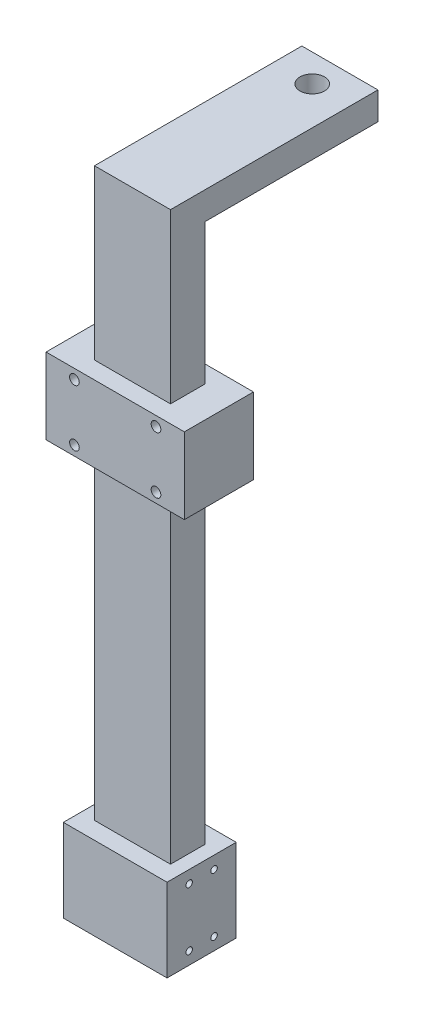
SolidWorks part; units mm, degrees
ref_plane "Front Plane" through (0, 0, 0) normal (0, 0, 1) x (1, 0, 0)
ref_plane "Top Plane" through (0, 0, 0) normal (0, 1, 0) x (1, 0, 0)
ref_plane "Right Plane" through (0, 0, 0) normal (1, 0, 0) x (0, 0, -1)
sketch "Sketch1" plane through (0, 0, 0) normal (0, 1, 0) x (1, 0, 0)
  line L1 (-6.985, -3.175) -> (6.985, -3.175)
  line L2 (-6.985, -3.175) -> (-6.985, 3.175)
  line L3 (-6.985, 3.175) -> (6.985, 3.175)
  line L4 (6.985, -3.175) -> (6.985, 3.175)
  line L5 (-6.985, -3.175) -> (6.985, 3.175) construction
  line L6 (-6.985, 3.175) -> (6.985, -3.175) construction
  point P0 (0, 0)
  dimension "D1" = 13.97
  dimension "D2" = 6.35
extrude "Boss-Extrude1" add sketch "Sketch1" along normal blind 114.3
sketch "Sketch3" plane through (0, 0, 3.175) normal (0, 0, 1) x (1, 0, 0)
  line L0 (0, 0) -> (0, 114.3) construction
  line L1 (-6.985, 114.3) -> (6.985, 114.3) construction
  line L3 (-12.7, 74.5062) -> (12.7, 74.5062)
  line L4 (-12.7, 74.5062) -> (-12.7, 88.4762)
  line L5 (-12.7, 88.4762) -> (12.7, 88.4762)
  line L6 (12.7, 74.5062) -> (12.7, 88.4762)
  line L7 (-12.7, 74.5062) -> (12.7, 88.4762) construction
  line L8 (-12.7, 88.4762) -> (12.7, 74.5062) construction
  point P5 (0, 81.4912)
  dimension "D1" = 13.97
  dimension "D2" = 25.4
extrude "Boss-Extrude3" add sketch "Sketch3" against normal blind 6.35
sketch "Sketch5" plane through (0, 0, 0) normal (1, 0, 0) x (0, 0, -1)
  line L0 (0, 0) -> (0, 74.5062) construction
  line L1 (3.175, 74.5062) -> (-3.175, 74.5062) construction
  line L2 (-3.175, 0) -> (3.175, 0) construction
  line L3 (-6.35, 0) -> (6.35, 0)
  line L4 (-6.35, 0) -> (-6.35, 15.24)
  line L5 (-6.35, 15.24) -> (6.35, 15.24)
  line L6 (6.35, 0) -> (6.35, 15.24)
  line L7 (-6.35, 0) -> (6.35, 15.24) construction
  line L8 (-6.35, 15.24) -> (6.35, 0) construction
  point P5 (0, 7.62)
  dimension "D1" = 12.7
  dimension "D2" = 15.24
extrude "Boss-Extrude5" add sketch "Sketch5" along normal blind 9.525 and the other way blind 9.525
sketch "Sketch6" plane through (0, 114.3, 0) normal (0, 1, 0) x (1, 0, 0)
  line L0 (6.985, -3.175) -> (6.985, 3.175) construction
  line L1 (-6.985, -3.175) -> (6.985, -3.175)
  line L2 (-6.985, -3.175) -> (-6.985, 34.925)
  line L3 (-6.985, 34.925) -> (6.985, 34.925)
  line L4 (6.985, -3.175) -> (6.985, 34.925)
  dimension "D1" = 38.1
extrude "Boss-Extrude6" add sketch "Sketch6" along normal blind 5.08
sketch "Sketch7" plane through (0, 119.38, 0) normal (0, 1, 0) x (1, 0, 0)
  line L0 (0, -3.175) -> (0, 34.925) construction
  line L1 (-6.985, -3.175) -> (6.985, -3.175) construction
  line L2 (6.985, 34.925) -> (-6.985, 34.925) construction
  circle A0 centre (0, 29.845) radius 2.25
  dimension "D1" = 4.5
  dimension "D2" = 5.08
extrude "Cut-Extrude1" cut sketch "Sketch7" against normal blind 5.08
sketch "Sketch8" plane through (-9.525, 0, 0) normal (-1, 0, 0) x (0, 0, 1)
  line L0 (0, 0) -> (0, 15.24) construction
  line L1 (-3.175, 15.24) -> (3.175, 15.24) construction
  line L2 (-6.35, 7.62) -> (6.35, 7.62) construction
  line L3 (-6.35, 0) -> (-6.35, 15.24) construction
  line L4 (6.35, 15.24) -> (6.35, 0) construction
  line L6 (-2.286, 2.286) -> (2.286, 2.286) construction
  line L7 (-2.286, 2.286) -> (-2.286, 12.954) construction
  line L8 (-2.286, 12.954) -> (2.286, 12.954) construction
  line L9 (2.286, 2.286) -> (2.286, 12.954) construction
  line L10 (-2.286, 2.286) -> (2.286, 12.954) construction
  line L11 (-2.286, 12.954) -> (2.286, 2.286) construction
  circle A0 centre (-2.286, 12.954) radius 0.5956
  circle A1 centre (2.286, 12.954) radius 0.5956
  circle A2 centre (2.286, 2.286) radius 0.5956
  circle A3 centre (-2.286, 2.286) radius 0.5956
  point P11 (0, 7.62)
  dimension "D3" = 1.1913
  dimension "D4" = 1.1913
  dimension "D5" = 1.1913
  dimension "D6" = 1.1913
  dimension "D1" = 5.334
  dimension "D2" = 2.286
extrude "Cut-Extrude2" cut sketch "Sketch8" against normal through all
sketch "Sketch9" plane through (0, 0, 3.175) normal (0, 0, 1) x (1, 0, 0)
  line L0 (-12.7, 81.4912) -> (12.7, 81.4912) construction
  line L1 (-12.7, 88.4762) -> (-12.7, 74.5062) construction
  line L2 (12.7, 74.5062) -> (12.7, 88.4762) construction
  line L3 (0, 119.38) -> (0, 0) construction
  line L4 (-6.985, 119.38) -> (6.985, 119.38) construction
  line L6 (-7.493, 76.2842) -> (7.493, 76.2842) construction
  line L7 (-7.493, 76.2842) -> (-7.493, 86.6982) construction
  line L8 (-7.493, 86.6982) -> (7.493, 86.6982) construction
  line L9 (7.493, 76.2842) -> (7.493, 86.6982) construction
  line L10 (-7.493, 76.2842) -> (7.493, 86.6982) construction
  line L11 (-7.493, 86.6982) -> (7.493, 76.2842) construction
  circle A0 centre (-7.493, 86.6982) radius 0.889
  circle A1 centre (7.493, 86.6982) radius 0.889
  circle A2 centre (7.493, 76.2842) radius 0.889
  circle A3 centre (-7.493, 76.2842) radius 0.889
  point P11 (0, 81.4912)
  dimension "D3" = 1.778
  dimension "D4" = 1.778
  dimension "D5" = 1.778
  dimension "D6" = 1.778
  dimension "D1" = 14.986
  dimension "D2" = 10.414
extrude "Cut-Extrude3" cut sketch "Sketch9" against normal through all
sketch "Sketch10" plane through (0, 0, 0) normal (0, 0, 1) x (1, 0, 0)
  line L1 (-12.7, 74.5062) -> (12.7, 74.5062)
  line L2 (-12.7, 74.5062) -> (-12.7, 88.4762)
  line L3 (-12.7, 88.4762) -> (12.7, 88.4762)
  line L4 (12.7, 74.5062) -> (12.7, 88.4762)
  circle A0 centre (7.493, 86.6982) radius 0.889
  circle A1 centre (7.493, 76.2842) radius 0.889
  circle A2 centre (-7.493, 76.2842) radius 0.889
  circle A3 centre (-7.493, 86.6982) radius 0.889
extrude "Boss-Extrude7" add sketch "Sketch10" along normal blind 6.35 and the other way blind 6.35 contours L1 L4 L3 L2 A3 A2 A1 A0
